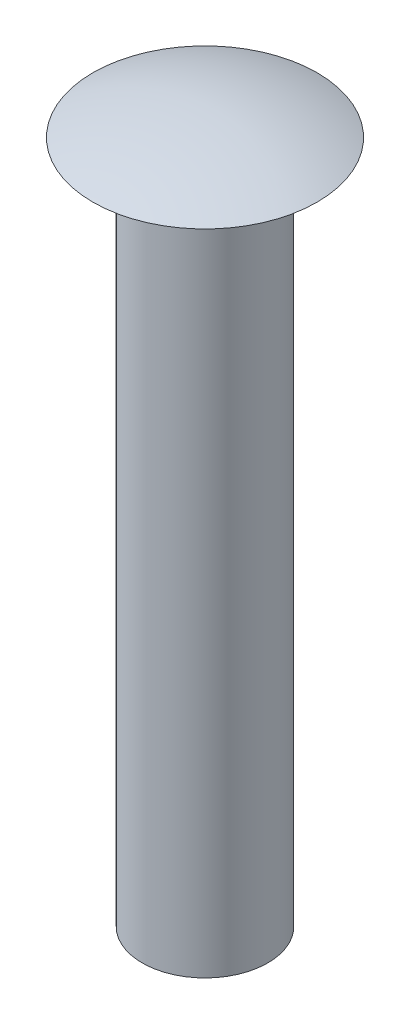
SolidWorks part; units mm, degrees
ref_plane "Front Plane" through (0, 0, 0) normal (0, 0, 1) x (1, 0, 0)
ref_plane "Top Plane" through (0, 0, 0) normal (0, 1, 0) x (1, 0, 0)
ref_plane "Right Plane" through (0, 0, 0) normal (1, 0, 0) x (0, 0, -1)
sketch "Sketch1" plane through (0, 0, 0) normal (0, 1, 0) x (1, 0, 0)
  circle A0 centre (0, 0) radius 1.75
  dimension "D1" = 3.5
extrude "Boss-Extrude1" add sketch "Sketch1" along normal blind 19.05
sketch "Sketch2" plane through (0, 0, 0) normal (0, 0, 1) x (1, 0, 0)
  line L0 (0, 19.05) -> (0, 19.685)
  line L1 (1.75, 19.05) -> (-1.75, 19.05) construction
  line L2 (0, 19.05) -> (3.125, 19.05)
  arc A0 (0, 19.685) -> (3.125, 19.05) centre (-0.0005, 11.6755) cw
  dimension "D1" = 0.635
  dimension "D2" = 3.125
revolve "Revolve1" add sketch "Sketch2" angle 360 about L0
